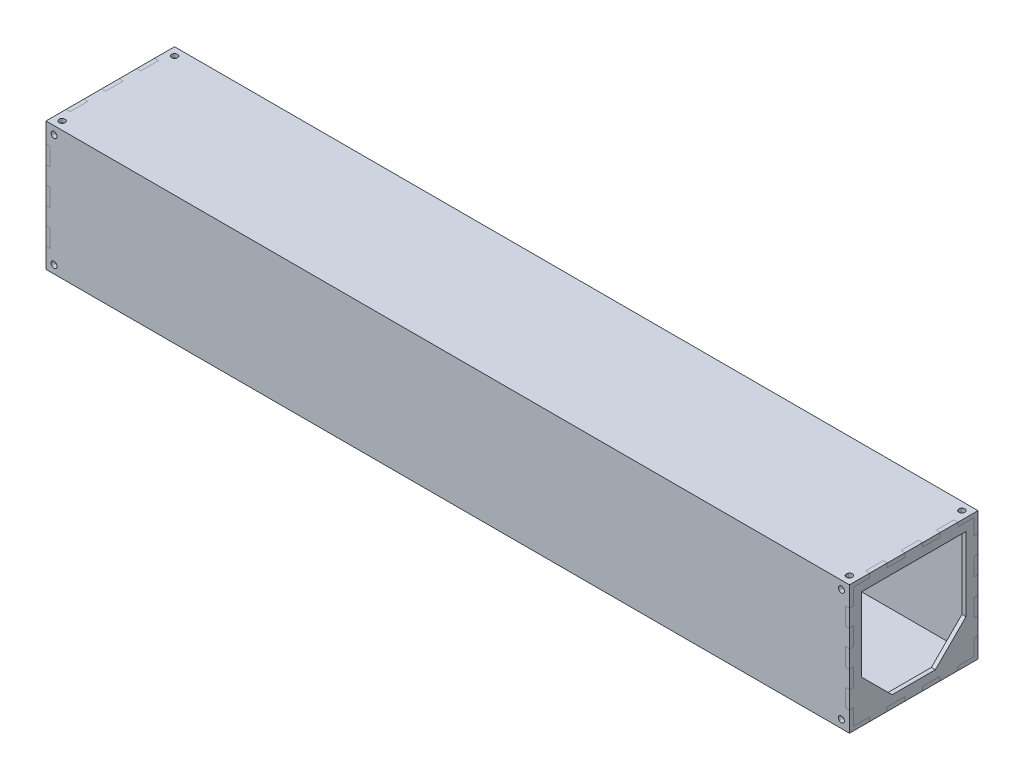
SolidWorks part; units mm, degrees
ref_plane "Front Plane" through (0, 0, 0) normal (0, 0, 1) x (1, 0, 0)
ref_plane "Top Plane" through (0, 0, 0) normal (0, 1, 0) x (1, 0, 0)
ref_plane "Right Plane" through (0, 0, 0) normal (1, 0, 0) x (0, 0, -1)
sketch "Sketch1" plane through (0, 0, 0) normal (1, 0, 0) x (0, 0, -1)
  line L0 (-98.425, 3.175) -> (-98.425, 98.425)
  line L1 (0, 0) -> (-101.6, 0)
  line L2 (0, 0) -> (0, 101.6)
  line L3 (0, 101.6) -> (-101.6, 101.6)
  line L4 (-101.6, 0) -> (-101.6, 101.6)
  line L5 (-3.175, 98.425) -> (-98.425, 98.425)
  line L6 (-3.175, 3.175) -> (-3.175, 98.425)
  line L7 (-3.175, 3.175) -> (-98.425, 3.175)
  dimension "D1" = 101.6
  dimension "D2" = 101.6
  dimension "D3" = 3.175
extrude "Boss-Extrude1" add sketch "Sketch1" along normal blind 628.65
sketch "Sketch3" plane through (0, 0, 0) normal (-1, 0, 0) x (0, 0, 1)
  line L0 (0, 85.725) -> (3.175, 85.725)
  line L1 (0, 0) -> (0, 101.6) construction
  line L2 (3.175, 3.175) -> (3.175, 98.425) construction
  line L3 (15.875, 101.6) -> (15.875, 98.425)
  line L4 (0, 101.6) -> (101.6, 101.6) construction
  line L5 (3.175, 98.425) -> (98.425, 98.425) construction
  line L6 (3.175, 50.8) -> (50.8, 50.8) construction
  line L7 (29.845, 101.6) -> (29.845, 98.425)
  line L8 (43.815, 101.6) -> (43.815, 98.425)
  line L9 (3.175, 98.425) -> (50.8, 50.8) construction
  line L10 (50.8, 50.8) -> (50.8, 98.425) construction
  line L11 (0, 57.785) -> (3.175, 57.785)
  line L12 (0, 71.755) -> (3.175, 71.755)
  line L13 (0, 85.725) -> (0, 101.6)
  line L14 (0, 101.6) -> (15.875, 101.6)
  line L15 (3.175, 85.725) -> (3.175, 98.425)
  line L16 (3.175, 98.425) -> (15.875, 98.425)
  line L17 (29.845, 101.6) -> (43.815, 101.6)
  line L18 (29.845, 98.425) -> (43.815, 98.425)
  line L19 (0, 71.755) -> (0, 57.785)
  line L20 (3.175, 71.755) -> (3.175, 57.785)
  line L21 (98.425, 71.755) -> (98.425, 57.785)
  line L22 (101.6, 71.755) -> (101.6, 57.785)
  line L23 (71.755, 98.425) -> (57.785, 98.425)
  line L24 (71.755, 101.6) -> (57.785, 101.6)
  line L25 (98.425, 98.425) -> (85.725, 98.425)
  line L26 (98.425, 85.725) -> (98.425, 98.425)
  line L27 (101.6, 101.6) -> (85.725, 101.6)
  line L28 (101.6, 85.725) -> (101.6, 101.6)
  line L29 (101.6, 71.755) -> (98.425, 71.755)
  line L30 (101.6, 57.785) -> (98.425, 57.785)
  line L31 (57.785, 101.6) -> (57.785, 98.425)
  line L32 (71.755, 101.6) -> (71.755, 98.425)
  line L33 (85.725, 101.6) -> (85.725, 98.425)
  line L34 (101.6, 85.725) -> (98.425, 85.725)
  line L35 (101.6, 15.875) -> (98.425, 15.875)
  line L36 (85.725, 0) -> (85.725, 3.175)
  line L37 (71.755, 0) -> (71.755, 3.175)
  line L38 (57.785, 0) -> (57.785, 3.175)
  line L39 (101.6, 43.815) -> (98.425, 43.815)
  line L40 (101.6, 29.845) -> (98.425, 29.845)
  line L41 (101.6, 15.875) -> (101.6, 0)
  line L42 (101.6, 0) -> (85.725, 0)
  line L43 (98.425, 15.875) -> (98.425, 3.175)
  line L44 (98.425, 3.175) -> (85.725, 3.175)
  line L45 (71.755, 0) -> (57.785, 0)
  line L46 (71.755, 3.175) -> (57.785, 3.175)
  line L47 (101.6, 29.845) -> (101.6, 43.815)
  line L48 (98.425, 29.845) -> (98.425, 43.815)
  line L49 (3.175, 29.845) -> (3.175, 43.815)
  line L50 (0, 29.845) -> (0, 43.815)
  line L51 (29.845, 3.175) -> (43.815, 3.175)
  line L52 (29.845, 0) -> (43.815, 0)
  line L53 (3.175, 3.175) -> (15.875, 3.175)
  line L54 (3.175, 15.875) -> (3.175, 3.175)
  line L55 (0, 0) -> (15.875, 0)
  line L56 (0, 15.875) -> (0, 0)
  line L57 (0, 29.845) -> (3.175, 29.845)
  line L58 (0, 43.815) -> (3.175, 43.815)
  line L59 (43.815, 0) -> (43.815, 3.175)
  line L60 (29.845, 0) -> (29.845, 3.175)
  line L61 (15.875, 0) -> (15.875, 3.175)
  line L62 (0, 15.875) -> (3.175, 15.875)
  dimension "D1" = 12.7
  dimension "D2" = 12.7
  dimension "D3" = 13.97
  dimension "D4" = 13.97
  dimension "D5" = 45
extrude "Boss-Extrude3" add sketch "Sketch3" along normal blind 3.175
sketch "Sketch4" plane through (0, 0, 0) normal (-1, 0, 0) x (0, 0, 1)
  line L0 (29.845, 98.425) -> (29.845, 101.6) construction
  line L1 (29.845, 101.6) -> (15.875, 101.6) construction
  line L2 (15.875, 101.6) -> (15.875, 98.425) construction
  line L3 (15.875, 98.425) -> (29.845, 98.425) construction
  line L4 (57.785, 98.425) -> (57.785, 101.6) construction
  line L5 (57.785, 101.6) -> (43.815, 101.6) construction
  line L6 (43.815, 101.6) -> (43.815, 98.425) construction
  line L7 (43.815, 98.425) -> (57.785, 98.425) construction
  line L8 (85.725, 98.425) -> (85.725, 101.6) construction
  line L9 (85.725, 101.6) -> (71.755, 101.6) construction
  line L10 (71.755, 101.6) -> (71.755, 98.425) construction
  line L11 (71.755, 98.425) -> (85.725, 98.425) construction
  line L12 (101.6, 85.725) -> (98.425, 85.725) construction
  line L13 (98.425, 85.725) -> (98.425, 71.755) construction
  line L14 (98.425, 71.755) -> (101.6, 71.755) construction
  line L15 (101.6, 71.755) -> (101.6, 85.725) construction
  line L16 (98.425, 43.815) -> (101.6, 43.815) construction
  line L17 (101.6, 43.815) -> (101.6, 57.785) construction
  line L18 (101.6, 57.785) -> (98.425, 57.785) construction
  line L19 (98.425, 57.785) -> (98.425, 43.815) construction
  line L20 (98.425, 15.875) -> (101.6, 15.875) construction
  line L21 (101.6, 15.875) -> (101.6, 29.845) construction
  line L22 (101.6, 29.845) -> (98.425, 29.845) construction
  line L23 (98.425, 29.845) -> (98.425, 15.875) construction
  line L24 (85.725, 0) -> (85.725, 3.175) construction
  line L25 (85.725, 3.175) -> (71.755, 3.175) construction
  line L26 (71.755, 3.175) -> (71.755, 0) construction
  line L27 (71.755, 0) -> (85.725, 0) construction
  line L28 (57.785, 0) -> (57.785, 3.175) construction
  line L29 (57.785, 3.175) -> (43.815, 3.175) construction
  line L30 (43.815, 3.175) -> (43.815, 0) construction
  line L31 (43.815, 0) -> (57.785, 0) construction
  line L32 (15.875, 3.175) -> (15.875, 0) construction
  line L33 (15.875, 0) -> (29.845, 0) construction
  line L34 (29.845, 0) -> (29.845, 3.175) construction
  line L35 (29.845, 3.175) -> (15.875, 3.175) construction
  line L36 (0, 15.875) -> (3.175, 15.875) construction
  line L37 (3.175, 15.875) -> (3.175, 29.845) construction
  line L38 (3.175, 29.845) -> (0, 29.845) construction
  line L39 (0, 29.845) -> (0, 15.875) construction
  line L40 (3.175, 57.785) -> (0, 57.785) construction
  line L41 (0, 57.785) -> (0, 43.815) construction
  line L42 (0, 43.815) -> (3.175, 43.815) construction
  line L43 (3.175, 43.815) -> (3.175, 57.785) construction
  line L44 (0, 71.755) -> (3.175, 71.755) construction
  line L45 (3.175, 71.755) -> (3.175, 85.725) construction
  line L46 (3.175, 85.725) -> (0, 85.725) construction
  line L47 (0, 85.725) -> (0, 71.755) construction
  line L48 (3.175, 57.785) -> (3.175, 71.755) construction
  line L49 (3.175, 29.845) -> (3.175, 43.815) construction
  line L50 (3.175, 3.175) -> (3.175, 15.875) construction
  line L51 (15.875, 3.175) -> (3.175, 3.175) construction
  line L52 (43.815, 3.175) -> (29.845, 3.175) construction
  line L53 (71.755, 3.175) -> (57.785, 3.175) construction
  line L54 (98.425, 3.175) -> (85.725, 3.175) construction
  line L55 (98.425, 15.875) -> (98.425, 3.175) construction
  line L56 (98.425, 43.815) -> (98.425, 29.845) construction
  line L57 (98.425, 71.755) -> (98.425, 57.785) construction
  line L58 (98.425, 98.425) -> (98.425, 85.725) construction
  line L59 (85.725, 98.425) -> (98.425, 98.425) construction
  line L60 (57.785, 98.425) -> (71.755, 98.425) construction
  line L61 (29.845, 98.425) -> (43.815, 98.425) construction
  line L62 (3.175, 98.425) -> (15.875, 98.425) construction
  line L63 (3.175, 85.725) -> (3.175, 98.425) construction
  line L64 (29.845, 98.425) -> (29.845, 101.6)
  line L65 (29.845, 101.6) -> (15.875, 101.6)
  line L66 (15.875, 101.6) -> (15.875, 98.425)
  line L67 (15.875, 98.425) -> (29.845, 98.425)
  line L68 (57.785, 98.425) -> (57.785, 101.6)
  line L69 (57.785, 101.6) -> (43.815, 101.6)
  line L70 (43.815, 101.6) -> (43.815, 98.425)
  line L71 (43.815, 98.425) -> (57.785, 98.425)
  line L72 (85.725, 98.425) -> (85.725, 101.6)
  line L73 (85.725, 101.6) -> (71.755, 101.6)
  line L74 (71.755, 101.6) -> (71.755, 98.425)
  line L75 (71.755, 98.425) -> (85.725, 98.425)
  line L76 (101.6, 85.725) -> (98.425, 85.725)
  line L77 (98.425, 85.725) -> (98.425, 71.755)
  line L78 (98.425, 71.755) -> (101.6, 71.755)
  line L79 (101.6, 71.755) -> (101.6, 85.725)
  line L80 (98.425, 43.815) -> (101.6, 43.815)
  line L81 (101.6, 43.815) -> (101.6, 57.785)
  line L82 (101.6, 57.785) -> (98.425, 57.785)
  line L83 (98.425, 57.785) -> (98.425, 43.815)
  line L84 (98.425, 15.875) -> (101.6, 15.875)
  line L85 (101.6, 15.875) -> (101.6, 29.845)
  line L86 (101.6, 29.845) -> (98.425, 29.845)
  line L87 (98.425, 29.845) -> (98.425, 15.875)
  line L88 (85.725, 0) -> (85.725, 3.175)
  line L89 (85.725, 3.175) -> (71.755, 3.175)
  line L90 (71.755, 3.175) -> (71.755, 0)
  line L91 (71.755, 0) -> (85.725, 0)
  line L92 (57.785, 0) -> (57.785, 3.175)
  line L93 (57.785, 3.175) -> (43.815, 3.175)
  line L94 (43.815, 3.175) -> (43.815, 0)
  line L95 (43.815, 0) -> (57.785, 0)
  line L96 (15.875, 3.175) -> (15.875, 0)
  line L97 (15.875, 0) -> (29.845, 0)
  line L98 (29.845, 0) -> (29.845, 3.175)
  line L99 (29.845, 3.175) -> (15.875, 3.175)
  line L100 (0, 15.875) -> (3.175, 15.875)
  line L101 (3.175, 15.875) -> (3.175, 29.845)
  line L102 (3.175, 29.845) -> (0, 29.845)
  line L103 (0, 29.845) -> (0, 15.875)
  line L104 (3.175, 57.785) -> (0, 57.785)
  line L105 (0, 57.785) -> (0, 43.815)
  line L106 (0, 43.815) -> (3.175, 43.815)
  line L107 (3.175, 43.815) -> (3.175, 57.785)
  line L108 (0, 71.755) -> (3.175, 71.755)
  line L109 (3.175, 71.755) -> (3.175, 85.725)
  line L110 (3.175, 85.725) -> (0, 85.725)
  line L111 (0, 85.725) -> (0, 71.755)
  line L112 (3.175, 57.785) -> (3.175, 71.755)
  line L113 (3.175, 29.845) -> (3.175, 43.815)
  line L114 (3.175, 3.175) -> (3.175, 15.875)
  line L115 (15.875, 3.175) -> (3.175, 3.175)
  line L116 (43.815, 3.175) -> (29.845, 3.175)
  line L117 (71.755, 3.175) -> (57.785, 3.175)
  line L118 (98.425, 3.175) -> (85.725, 3.175)
  line L119 (98.425, 15.875) -> (98.425, 3.175)
  line L120 (98.425, 43.815) -> (98.425, 29.845)
  line L121 (98.425, 71.755) -> (98.425, 57.785)
  line L122 (98.425, 98.425) -> (98.425, 85.725)
  line L123 (85.725, 98.425) -> (98.425, 98.425)
  line L124 (57.785, 98.425) -> (71.755, 98.425)
  line L125 (29.845, 98.425) -> (43.815, 98.425)
  line L126 (3.175, 98.425) -> (15.875, 98.425)
  line L127 (3.175, 85.725) -> (3.175, 98.425)
  line L129 (3.175, 98.425) -> (98.425, 98.425)
  line L130 (3.175, 98.425) -> (3.175, 3.175)
  line L131 (3.175, 3.175) -> (98.425, 3.175)
  line L132 (98.425, 98.425) -> (98.425, 3.175)
  line M5 (0, 71.755) -> (3.175, 71.755)
  line M6 (3.175, 71.755) -> (3.175, 85.725)
  line M7 (3.175, 85.725) -> (0, 85.725)
  line M8 (0, 85.725) -> (0, 71.755)
extrude "Boss-Extrude4" add sketch "Sketch4" along normal blind 3.175 separate body contours L66 L67 L64 L65 | L127 L112 L107 L113 L101 L114 L115 L99 L116 L93 L117 L89 L118 L119 L87 L120 L83 L121 L77 L122 L123 L75 L124 L71 L125 L67 L126 M6 | L70 L71 L68 L69 | L74 L75 L72 L73 | L78 L79 L76 L77 | L82 L83 L80 L81 | L86 L87 L84 L85 | L90 L91 L88 L89 | L94 L95 L92 L93 | L98 L99 L96 L97 | L102 L103 L100 L101 | L106 L107 L104 L105 | M8 M5 M6 M7
sketch "Sketch5" plane through (628.65, 0, 0) normal (1, 0, 0) x (0, 0, -1)
  line L0 (-92.075, 33.7033) -> (-67.8967, 9.525)
  line L1 (-92.075, 92.075) -> (-9.525, 92.075)
  line L2 (-92.075, 92.075) -> (-92.075, 9.525) construction
  line L3 (-92.075, 9.525) -> (-9.525, 9.525) construction
  line L4 (-9.525, 92.075) -> (-9.525, 9.525) construction
  line L5 (-33.7033, 9.525) -> (-9.525, 33.7033)
  line L6 (-67.8967, 9.525) -> (-33.7033, 9.525)
  line L7 (-92.075, 33.7033) -> (-92.075, 92.075)
  line L8 (-9.525, 92.075) -> (-9.525, 33.7033)
  line L52 (-15.875, 98.425) -> (-15.875, 101.6)
  line L53 (-3.175, 98.425) -> (-15.875, 98.425)
  line L54 (-3.175, 85.725) -> (-3.175, 98.425)
  line L55 (0, 85.725) -> (-3.175, 85.725)
  line L56 (0, 71.755) -> (0, 85.725)
  line L57 (-3.175, 71.755) -> (0, 71.755)
  line L58 (-3.175, 57.785) -> (-3.175, 71.755)
  line L59 (0, 57.785) -> (-3.175, 57.785)
  line L60 (0, 43.815) -> (0, 57.785)
  line L61 (-3.175, 43.815) -> (0, 43.815)
  line L62 (-3.175, 29.845) -> (-3.175, 43.815)
  line L63 (0, 29.845) -> (-3.175, 29.845)
  line L64 (0, 15.875) -> (0, 29.845)
  line L65 (-3.175, 15.875) -> (0, 15.875)
  line L66 (-3.175, 3.175) -> (-3.175, 15.875)
  line L67 (-15.875, 3.175) -> (-3.175, 3.175)
  line L68 (-15.875, 0) -> (-15.875, 3.175)
  line L69 (-29.845, 0) -> (-15.875, 0)
  line L70 (-29.845, 3.175) -> (-29.845, 0)
  line L71 (-43.815, 3.175) -> (-29.845, 3.175)
  line L72 (-43.815, 0) -> (-43.815, 3.175)
  line L73 (-57.785, 0) -> (-43.815, 0)
  line L74 (-57.785, 3.175) -> (-57.785, 0)
  line L75 (-71.755, 3.175) -> (-57.785, 3.175)
  line L76 (-71.755, 0) -> (-71.755, 3.175)
  line L77 (-85.725, 0) -> (-71.755, 0)
  line L78 (-85.725, 3.175) -> (-85.725, 0)
  line L79 (-98.425, 3.175) -> (-85.725, 3.175)
  line L80 (-98.425, 15.875) -> (-98.425, 3.175)
  line L81 (-101.6, 15.875) -> (-98.425, 15.875)
  line L82 (-101.6, 29.845) -> (-101.6, 15.875)
  line L83 (-98.425, 29.845) -> (-101.6, 29.845)
  line L84 (-98.425, 43.815) -> (-98.425, 29.845)
  line L85 (-101.6, 43.815) -> (-98.425, 43.815)
  line L86 (-101.6, 57.785) -> (-101.6, 43.815)
  line L87 (-98.425, 57.785) -> (-101.6, 57.785)
  line L88 (-98.425, 71.755) -> (-98.425, 57.785)
  line L89 (-101.6, 71.755) -> (-98.425, 71.755)
  line L90 (-101.6, 85.725) -> (-101.6, 71.755)
  line L91 (-98.425, 85.725) -> (-101.6, 85.725)
  line L92 (-98.425, 98.425) -> (-98.425, 85.725)
  line L93 (-85.725, 98.425) -> (-98.425, 98.425)
  line L94 (-85.725, 101.6) -> (-85.725, 98.425)
  line L95 (-71.755, 101.6) -> (-85.725, 101.6)
  line L96 (-71.755, 98.425) -> (-71.755, 101.6)
  line L97 (-57.785, 98.425) -> (-71.755, 98.425)
  line L98 (-57.785, 101.6) -> (-57.785, 98.425)
  line L99 (-43.815, 101.6) -> (-57.785, 101.6)
  line L100 (-43.815, 98.425) -> (-43.815, 101.6)
  line L101 (-29.845, 98.425) -> (-43.815, 98.425)
  line L102 (-29.845, 101.6) -> (-29.845, 98.425)
  line L103 (-15.875, 101.6) -> (-29.845, 101.6)
  line L104 (-15.875, 98.425) -> (-15.875, 101.6)
  line L105 (-3.175, 98.425) -> (-15.875, 98.425)
  line L106 (-3.175, 85.725) -> (-3.175, 98.425)
  line L107 (0, 85.725) -> (-3.175, 85.725)
  line L108 (0, 71.755) -> (0, 85.725)
  line L109 (-3.175, 71.755) -> (0, 71.755)
  line L110 (-3.175, 57.785) -> (-3.175, 71.755)
  line L111 (0, 57.785) -> (-3.175, 57.785)
  line L112 (0, 43.815) -> (0, 57.785)
  line L113 (-3.175, 43.815) -> (0, 43.815)
  line L114 (-3.175, 29.845) -> (-3.175, 43.815)
  line L115 (0, 29.845) -> (-3.175, 29.845)
  line L116 (0, 15.875) -> (0, 29.845)
  line L117 (-3.175, 15.875) -> (0, 15.875)
  line L118 (-3.175, 3.175) -> (-3.175, 15.875)
  line L119 (-15.875, 3.175) -> (-3.175, 3.175)
  line L120 (-15.875, 0) -> (-15.875, 3.175)
  line L121 (-29.845, 0) -> (-15.875, 0)
  line L122 (-29.845, 3.175) -> (-29.845, 0)
  line L123 (-43.815, 3.175) -> (-29.845, 3.175)
  line L124 (-43.815, 0) -> (-43.815, 3.175)
  line L125 (-57.785, 0) -> (-43.815, 0)
  line L126 (-57.785, 3.175) -> (-57.785, 0)
  line L127 (-71.755, 3.175) -> (-57.785, 3.175)
  line L128 (-71.755, 0) -> (-71.755, 3.175)
  line L129 (-85.725, 0) -> (-71.755, 0)
  line L130 (-85.725, 3.175) -> (-85.725, 0)
  line L131 (-98.425, 3.175) -> (-85.725, 3.175)
  line L132 (-98.425, 15.875) -> (-98.425, 3.175)
  line L133 (-101.6, 15.875) -> (-98.425, 15.875)
  line L134 (-101.6, 29.845) -> (-101.6, 15.875)
  line L135 (-98.425, 29.845) -> (-101.6, 29.845)
  line L136 (-98.425, 43.815) -> (-98.425, 29.845)
  line L137 (-101.6, 43.815) -> (-98.425, 43.815)
  line L138 (-101.6, 57.785) -> (-101.6, 43.815)
  line L139 (-98.425, 57.785) -> (-101.6, 57.785)
  line L140 (-98.425, 71.755) -> (-98.425, 57.785)
  line L141 (-101.6, 71.755) -> (-98.425, 71.755)
  line L142 (-101.6, 85.725) -> (-101.6, 71.755)
  line L143 (-98.425, 85.725) -> (-101.6, 85.725)
  line L144 (-98.425, 98.425) -> (-98.425, 85.725)
  line L145 (-85.725, 98.425) -> (-98.425, 98.425)
  line L146 (-85.725, 101.6) -> (-85.725, 98.425)
  line L147 (-71.755, 101.6) -> (-85.725, 101.6)
  line L148 (-71.755, 98.425) -> (-71.755, 101.6)
  line L149 (-57.785, 98.425) -> (-71.755, 98.425)
  line L150 (-57.785, 101.6) -> (-57.785, 98.425)
  line L151 (-43.815, 101.6) -> (-57.785, 101.6)
  line L152 (-43.815, 98.425) -> (-43.815, 101.6)
  line L153 (-29.845, 98.425) -> (-43.815, 98.425)
  line L154 (-29.845, 101.6) -> (-29.845, 98.425)
  line L155 (-15.875, 101.6) -> (-29.845, 101.6)
  circle A0 centre (-50.8, 50.8) radius 41.275
  line M56 (0, 0) -> (0, 101.6)
  line M57 (0, 101.6) -> (-101.6, 101.6)
  line M58 (-101.6, 101.6) -> (-101.6, 0)
  line M59 (-101.6, 0) -> (0, 0)
  line M60 (-3.175, 98.425) -> (-3.175, 3.175)
  line M61 (-3.175, 3.175) -> (-98.425, 3.175)
  line M62 (-98.425, 3.175) -> (-98.425, 98.425)
  line M63 (-98.425, 98.425) -> (-3.175, 98.425)
  dimension "D2" = 82.55
  dimension "D3" = 82.55
  dimension "D4" = 6.35
  dimension "D5" = 6.35
  dimension "D6" = 45
  dimension "D7" = 45
  dimension "D1" = 0
extrude "Boss-Extrude5" add sketch "Sketch5" along normal blind 3.175 separate body contours L1 L8 L5 L6 L0 L7 M60 M63 M62 M61 | L135 L133 M62 M58 | L139 L137 M62 M58 | L143 L141 M62 M58 | L148 L146 M63 M57 | L152 L150 M63 M57 | L154 L104 M57 M63 | L109 L107 M60 M56 | L113 L111 M60 M56 | L117 L115 M60 M56 | L122 L120 M61 M59 | L126 L124 M61 M59 | L130 L128 M61 M59
sketch "Sketch6" plane through (628.65, 0, 0) normal (1, 0, 0) x (0, 0, -1)
  line L0 (-101.6, 29.845) -> (-101.6, 43.815) construction
  line L1 (-101.6, 43.815) -> (-98.425, 43.815) construction
  line L2 (-98.425, 43.815) -> (-98.425, 29.845) construction
  line L3 (-98.425, 29.845) -> (-101.6, 29.845) construction
  line L4 (-101.6, 71.755) -> (-98.425, 71.755) construction
  line L5 (-98.425, 71.755) -> (-98.425, 57.785) construction
  line L6 (-98.425, 57.785) -> (-101.6, 57.785) construction
  line L7 (-101.6, 57.785) -> (-101.6, 71.755) construction
  line L8 (-98.425, 98.425) -> (-98.425, 85.725) construction
  line L9 (-98.425, 85.725) -> (-101.6, 85.725) construction
  line L10 (-101.6, 85.725) -> (-101.6, 101.6) construction
  line L11 (-101.6, 101.6) -> (-85.725, 101.6) construction
  line L12 (-85.725, 101.6) -> (-85.725, 98.425) construction
  line L13 (-85.725, 98.425) -> (-98.425, 98.425) construction
  line L14 (-71.755, 98.425) -> (-71.755, 101.6) construction
  line L15 (-71.755, 101.6) -> (-57.785, 101.6) construction
  line L16 (-57.785, 101.6) -> (-57.785, 98.425) construction
  line L17 (-57.785, 98.425) -> (-71.755, 98.425) construction
  line L18 (-43.815, 101.6) -> (-29.845, 101.6) construction
  line L19 (-29.845, 101.6) -> (-29.845, 98.425) construction
  line L20 (-29.845, 98.425) -> (-43.815, 98.425) construction
  line L21 (-43.815, 98.425) -> (-43.815, 101.6) construction
  line L22 (0, 101.6) -> (0, 85.725) construction
  line L23 (0, 85.725) -> (-3.175, 85.725) construction
  line L24 (-3.175, 85.725) -> (-3.175, 98.425) construction
  line L25 (-3.175, 98.425) -> (-15.875, 98.425) construction
  line L26 (-15.875, 98.425) -> (-15.875, 101.6) construction
  line L27 (-15.875, 101.6) -> (0, 101.6) construction
  line L28 (0, 71.755) -> (0, 57.785) construction
  line L29 (0, 57.785) -> (-3.175, 57.785) construction
  line L30 (-3.175, 57.785) -> (-3.175, 71.755) construction
  line L31 (-3.175, 71.755) -> (0, 71.755) construction
  line L32 (0, 29.845) -> (-3.175, 29.845) construction
  line L33 (-3.175, 29.845) -> (-3.175, 43.815) construction
  line L34 (-3.175, 43.815) -> (0, 43.815) construction
  line L35 (0, 43.815) -> (0, 29.845) construction
  line L36 (-3.175, 3.175) -> (-3.175, 15.875) construction
  line L37 (-3.175, 15.875) -> (0, 15.875) construction
  line L38 (0, 15.875) -> (0, 0) construction
  line L39 (0, 0) -> (-15.875, 0) construction
  line L40 (-15.875, 0) -> (-15.875, 3.175) construction
  line L41 (-15.875, 3.175) -> (-3.175, 3.175) construction
  line L42 (-29.845, 3.175) -> (-29.845, 0) construction
  line L43 (-29.845, 0) -> (-43.815, 0) construction
  line L44 (-43.815, 0) -> (-43.815, 3.175) construction
  line L45 (-43.815, 3.175) -> (-29.845, 3.175) construction
  line L46 (-57.785, 0) -> (-71.755, 0) construction
  line L47 (-71.755, 0) -> (-71.755, 3.175) construction
  line L48 (-71.755, 3.175) -> (-57.785, 3.175) construction
  line L49 (-57.785, 3.175) -> (-57.785, 0) construction
  line L50 (-101.6, 0) -> (-101.6, 15.875) construction
  line L51 (-101.6, 15.875) -> (-98.425, 15.875) construction
  line L52 (-98.425, 15.875) -> (-98.425, 3.175) construction
  line L53 (-98.425, 3.175) -> (-85.725, 3.175) construction
  line L54 (-85.725, 3.175) -> (-85.725, 0) construction
  line L55 (-85.725, 0) -> (-101.6, 0) construction
  line L56 (-101.6, 29.845) -> (-101.6, 43.815)
  line L57 (-101.6, 43.815) -> (-98.425, 43.815)
  line L58 (-98.425, 43.815) -> (-98.425, 29.845)
  line L59 (-98.425, 29.845) -> (-101.6, 29.845)
  line L60 (-101.6, 71.755) -> (-98.425, 71.755)
  line L61 (-98.425, 71.755) -> (-98.425, 57.785)
  line L62 (-98.425, 57.785) -> (-101.6, 57.785)
  line L63 (-101.6, 57.785) -> (-101.6, 71.755)
  line L64 (-98.425, 98.425) -> (-98.425, 85.725)
  line L65 (-98.425, 85.725) -> (-101.6, 85.725)
  line L66 (-101.6, 85.725) -> (-101.6, 101.6)
  line L67 (-101.6, 101.6) -> (-85.725, 101.6)
  line L68 (-85.725, 101.6) -> (-85.725, 98.425)
  line L69 (-85.725, 98.425) -> (-98.425, 98.425)
  line L70 (-71.755, 98.425) -> (-71.755, 101.6)
  line L71 (-71.755, 101.6) -> (-57.785, 101.6)
  line L72 (-57.785, 101.6) -> (-57.785, 98.425)
  line L73 (-57.785, 98.425) -> (-71.755, 98.425)
  line L74 (-43.815, 101.6) -> (-29.845, 101.6)
  line L75 (-29.845, 101.6) -> (-29.845, 98.425)
  line L76 (-29.845, 98.425) -> (-43.815, 98.425)
  line L77 (-43.815, 98.425) -> (-43.815, 101.6)
  line L78 (0, 101.6) -> (0, 85.725)
  line L79 (0, 85.725) -> (-3.175, 85.725)
  line L80 (-3.175, 85.725) -> (-3.175, 98.425)
  line L81 (-3.175, 98.425) -> (-15.875, 98.425)
  line L82 (-15.875, 98.425) -> (-15.875, 101.6)
  line L83 (-15.875, 101.6) -> (0, 101.6)
  line L84 (0, 71.755) -> (0, 57.785)
  line L85 (0, 57.785) -> (-3.175, 57.785)
  line L86 (-3.175, 57.785) -> (-3.175, 71.755)
  line L87 (-3.175, 71.755) -> (0, 71.755)
  line L88 (0, 29.845) -> (-3.175, 29.845)
  line L89 (-3.175, 29.845) -> (-3.175, 43.815)
  line L90 (-3.175, 43.815) -> (0, 43.815)
  line L91 (0, 43.815) -> (0, 29.845)
  line L92 (-3.175, 3.175) -> (-3.175, 15.875)
  line L93 (-3.175, 15.875) -> (0, 15.875)
  line L94 (0, 15.875) -> (0, 0)
  line L95 (0, 0) -> (-15.875, 0)
  line L96 (-15.875, 0) -> (-15.875, 3.175)
  line L97 (-15.875, 3.175) -> (-3.175, 3.175)
  line L98 (-29.845, 3.175) -> (-29.845, 0)
  line L99 (-29.845, 0) -> (-43.815, 0)
  line L100 (-43.815, 0) -> (-43.815, 3.175)
  line L101 (-43.815, 3.175) -> (-29.845, 3.175)
  line L102 (-57.785, 0) -> (-71.755, 0)
  line L103 (-71.755, 0) -> (-71.755, 3.175)
  line L104 (-71.755, 3.175) -> (-57.785, 3.175)
  line L105 (-57.785, 3.175) -> (-57.785, 0)
  line L106 (-101.6, 0) -> (-101.6, 15.875)
  line L107 (-101.6, 15.875) -> (-98.425, 15.875)
  line L108 (-98.425, 15.875) -> (-98.425, 3.175)
  line L109 (-98.425, 3.175) -> (-85.725, 3.175)
  line L110 (-85.725, 3.175) -> (-85.725, 0)
  line L111 (-85.725, 0) -> (-101.6, 0)
extrude "Boss-Extrude6" add sketch "Sketch6" along normal blind 3.175
sketch "Sketch7" plane through (0, 0, 0) normal (0, 0, -1) x (-1, 0, 0)
  line L0 (-628.65, 50.8) -> (-593.7859, 50.8)
  line L1 (-628.65, 43.815) -> (-628.65, 57.785) construction
  line L2 (-314.325, 101.6) -> (-314.325, 65.2781)
  line L3 (-631.825, 101.6) -> (3.175, 101.6) construction
  line L4 (-631.825, 85.725) -> (-631.825, 101.6) construction
  circle A0 centre (-625.475, 95.25) radius 2.3812
  circle A1 centre (-625.475, 6.35) radius 2.3812
  circle A2 centre (-3.175, 6.35) radius 2.3813
  circle A3 centre (-3.175, 95.25) radius 2.3812
  dimension "D1" = 4.7625
  dimension "D2" = 6.35
  dimension "D3" = 6.35
extrude "Cut-Extrude1" cut sketch "Sketch7" against normal through all contours A0 | A1 | A3 | A2
sketch "Sketch8" plane through (0, 101.6, 0) normal (0, 1, 0) x (1, 0, 0)
  line L0 (631.825, 0) -> (-3.175, 0) construction
  line L1 (-3.175, -15.875) -> (-3.175, 0) construction
  line L2 (0, -50.8) -> (30.0165, -50.8)
  line L3 (0, -43.815) -> (0, -57.785) construction
  line L4 (314.325, 0) -> (314.325, -27.8872)
  circle A0 centre (3.175, -6.35) radius 2.3813
  circle A1 centre (3.175, -95.25) radius 2.3813
  circle A2 centre (625.475, -95.25) radius 2.3812
  circle A3 centre (625.475, -6.35) radius 2.3812
  dimension "D1" = 4.7625
  dimension "D2" = 6.35
  dimension "D3" = 6.35
extrude "Cut-Extrude2" cut sketch "Sketch8" against normal through all contours A0 | A3 | A2 | A1
